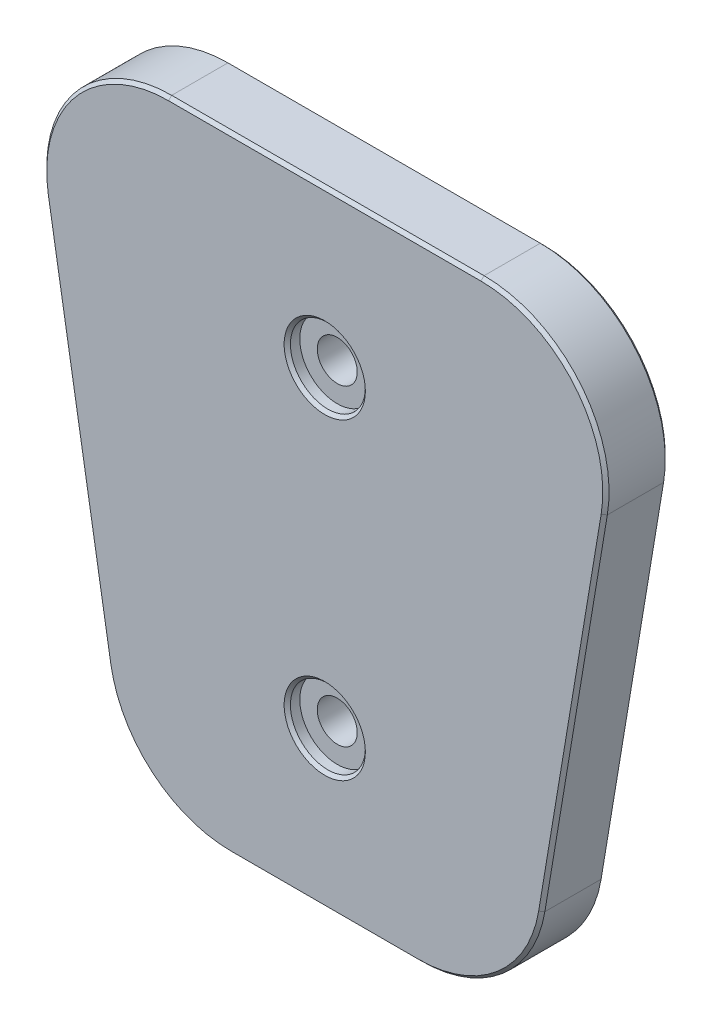
SolidWorks part; units mm, degrees
ref_plane "Front Plane" through (0, 0, 0) normal (0, 0, 1) x (1, 0, 0)
ref_plane "Top Plane" through (0, 0, 0) normal (0, 1, 0) x (1, 0, 0)
ref_plane "Right Plane" through (0, 0, 0) normal (1, 0, 0) x (0, 0, -1)
sketch "Sketch3" plane through (0, 0, 0) normal (0, 0, 1) x (1, 0, 0)
  line L0 (-6.3553, -23.288) -> (3.6447, -83.288)
  line L1 (13.3726, 0) -> (63.3726, 0)
  line L5 (23.3726, -100) -> (53.3726, -100)
  line L6 (73.1005, -83.288) -> (83.1005, -23.288)
  line L7 (38.3726, 0) -> (38.3726, -173.3588) construction
  arc A0 (63.3726, 0) -> (83.1005, -23.288) centre (63.3726, -20) cw
  arc A1 (13.3726, 0) -> (-6.3553, -23.288) centre (13.3726, -20) ccw
  arc A2 (53.3726, -100) -> (73.1005, -83.288) centre (53.3726, -80) ccw
  arc A3 (3.6447, -83.288) -> (23.3726, -100) centre (23.3726, -80) ccw
  point P7 (120, 0)
  point P10 (0, 0)
  point P13 (38.3726, -100)
  dimension "D3" = 20
  dimension "D5" = 20
  dimension "D6" = 30
  dimension "D1" = 50
  dimension "D2" = 100
  dimension "D4" = 0
extrude "Boss-Extrude1" add sketch "Sketch3" along normal blind 10 contours A3 L5 A2 L6 A0 L1 A1 L0
sketch "Sketch4" plane through (0, 0, 10) normal (0, 0, 1) x (1, 0, 0)
  line L0 (38.3726, 0) -> (38.3726, -50) construction
  line L1 (13.3726, 0) -> (63.3726, 0) construction
  line L2 (23.3726, -100) -> (53.3726, -100) construction
  line L3 (38.3726, 0) -> (38.3726, -50) construction
  line L4 (38.3726, -50) -> (38.3726, -100) construction
  line L5 (38.3726, -50) -> (38.3726, -100) construction
  circle A1 centre (38.3726, -25) radius 6
  circle A2 centre (38.3726, -75) radius 6
  dimension "D1" = 12
  dimension "D3" = 12
  dimension "D2" = 25
  dimension "D4" = 25
extrude "Cut-Extrude1" cut sketch "Sketch4" against normal blind 2
sketch "Sketch5" plane through (0, 0, 8) normal (0, 0, 1) x (1, 0, 0)
  circle A0 centre (38.3726, -25) radius 3.2
  circle A2 centre (38.3726, -75) radius 3.2
  dimension "D1" = 6.4
  dimension "D3" = 6.4
extrude "Cut-Extrude2" cut sketch "Sketch5" against normal through all
chamfer "Chamfer1" distance 0.5 angle 45 20 edges at (10.4451, -95.2604, 0) (38.3726, -100, 0) (66.3001, -95.2604, 0) (78.1005, -53.288, 0) (78.633, -7.0725, 0) (38.3726, 0, 0) (-1.8878, -7.0725, 0) (-1.3553, -53.288, 0) (41.5726, -75, 0) (41.5726, -25, 0) (-1.8878, -7.0725, 10) (38.3726, 0, 10) (78.633, -7.0725, 10) (78.1005, -53.288, 10) (66.3001, -95.2604, 10) (38.3726, -100, 10) (10.4451, -95.2604, 10) (-1.3553, -53.288, 10) (44.3726, -25, 10) (44.3726, -75, 10)
equation "\"D3@Sketch4\"= \"D1@Sketch4\""
equation "\"D3@Sketch5\"=\"D1@Sketch5\""
